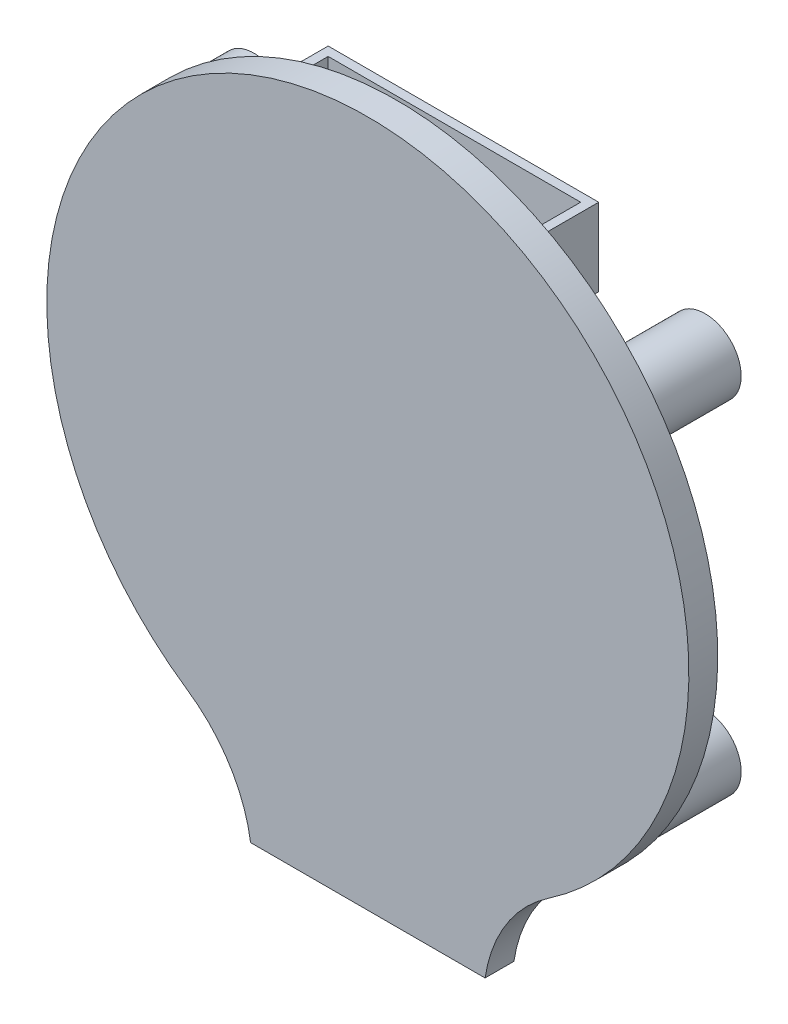
SolidWorks part; units mm, degrees
ref_plane "Plan de face" through (0, 0, 0) normal (0, 0, 1) x (1, 0, 0)
ref_plane "Plan de dessus" through (0, 0, 0) normal (0, 1, 0) x (1, 0, 0)
ref_plane "Plan de droite" through (0, 0, 0) normal (1, 0, 0) x (0, 0, -1)
sketch "Contour_Écran" plane through (0, 0, 0) normal (0, 0, 1) x (1, 0, 0)
  line L0 (10.0051, 0) -> (10.0051, -22.8841) construction
  line L5 (0, 0) -> (10.0051, 0) construction
  line L6 (0, 0) -> (-10.0051, 0) construction
  line L7 (-10.0051, 0) -> (-10.0051, -22.8841) construction
  line L8 (-6.5, -20.3) -> (6.5, -20.3) construction
  line L9 (0, 0) -> (-10.0051, -14.722) construction
  line L10 (0, 0) -> (10.0051, -14.722) construction
  line L11 (-6.5, -20.3) -> (6.5, -20.3)
  line L12 (0, 0) -> (-6.5, -20.3) construction
  line L13 (0, 0) -> (6.5, -20.3) construction
  arc A0 (10.0051, -14.722) -> (-10.0051, -14.722) centre (0, 0) ccw
  arc A1 (-10.0051, -14.722) -> (-6.5, -20.3) centre (-14.6194, -21.5118) cw
  arc A2 (10.0051, -14.722) -> (6.5, -20.3) centre (14.6194, -21.5118) ccw
  point P4 (0, -20.3)
  dimension "D1" = 17.8
  dimension "D2" = 13
  dimension "D3" = 20.3
  dimension "D4" = 55.8
  dimension "D5" = 55.8
extrude "Boss.-Extru.1_Contour_Écran" add sketch "Contour_Écran" along normal blind 1.6
sketch "Entretoises" plane through (0, 0, 0) normal (0, 0, -1) x (-1, 0, 0)
  line L1 (-12.5, -9.5) -> (12.5, -9.5) construction
  line L2 (-12.5, -9.5) -> (-12.5, 9.5) construction
  line L3 (-12.5, 9.5) -> (12.5, 9.5) construction
  line L4 (12.5, -9.5) -> (12.5, 9.5) construction
  line L5 (-12.5, -9.5) -> (12.5, 9.5) construction
  line L6 (-12.5, 9.5) -> (12.5, -9.5) construction
  circle A0 centre (-12.5, 9.5) radius 2
  circle A1 centre (12.5, 9.5) radius 2
  circle A2 centre (12.5, -9.5) radius 2
  circle A3 centre (-12.5, -9.5) radius 2
  point P0 (0, 0)
  dimension "D3" = 4
  dimension "D1" = 19
  dimension "D2" = 25
  dimension "D4" = 2
  dimension "D5" = 2
extrude "Boss.-Extru.1_Entretoises" add sketch "Entretoises" along normal blind 4.6
sketch "Trous_Vis_M2" plane through (0, 0, -4.6) normal (0, 0, -1) x (-1, 0, 0)
  circle A0 centre (-12.5, 9.5) radius 1
  circle A1 centre (12.5, 9.5) radius 1
  circle A2 centre (12.5, -9.5) radius 1
  circle A3 centre (-12.5, -9.5) radius 1
  dimension "D1" = 2
  dimension "D2" = 2
  dimension "D3" = 2
extrude "Enlèv. mat.-Extru.1_Trous_Vis_M2" cut sketch "Trous_Vis_M2" against normal up to surface (4.6 mm away) up to face at (10.5, -9.5, 0)
sketch "Connecteurs_Blancs" plane through (0, 0, 0) normal (0, 0, -1) x (-1, 0, 0)
  line L0 (-24.5608, 17.8) -> (30.8028, 17.8) construction
  line L1 (-7.5, 10.5) -> (7.5, 10.5)
  line L2 (-7.5, 10.5) -> (-7.5, 14.8)
  line L3 (-7.5, 14.8) -> (7.5, 14.8)
  line L4 (7.5, 10.5) -> (7.5, 14.8)
  line L5 (-7.5, 10.5) -> (7.5, 14.8) construction
  line L6 (-7.5, 14.8) -> (7.5, 10.5) construction
  line L7 (-5, -8.3) -> (5, -8.3)
  line L8 (-5, -8.3) -> (-5, -4)
  line L9 (-5, -4) -> (5, -4)
  line L10 (5, -8.3) -> (5, -4)
  line L11 (-5, -8.3) -> (5, -4) construction
  line L12 (-5, -4) -> (5, -8.3) construction
  line L13 (0, 17.8) -> (0, 14.8) construction
  line L14 (0, 10.5) -> (0, -4) construction
  circle A0 centre (0, 0) radius 17.8 construction
  arc A1 (10.0051, -14.722) -> (-10.0051, -14.722) centre (0, 0) ccw construction
  point P0 (0, 12.65)
  point P5 (0, -6.15)
  point P20 (0, 14.8)
  point P23 (0, -4)
  dimension "D1" = 4.3
  dimension "D2" = 10
  dimension "D3" = 4.3
  dimension "D4" = 15
  dimension "D5" = 3
  dimension "D6" = 14.5
extrude "Boss.-Extru.2_Connecteurs_Blancs" add sketch "Connecteurs_Blancs" along normal blind 3.7
sketch "Ouverture_gros_connecteur_blanc" plane through (0, 14.8, 0) normal (0, 1, 0) x (1, 0, 0)
  line L0 (-7.5, 3.7) -> (7.5, 0) construction
  line L1 (-7.5, 0) -> (7.5, 3.7) construction
  line L2 (-7.5, 3.7) -> (7.5, 3.7) construction
  line L3 (-7, 0.5) -> (7, 0.5)
  line L4 (-7, 0.5) -> (-7, 3.2)
  line L5 (-7, 3.2) -> (7, 3.2)
  line L6 (7, 0.5) -> (7, 3.2)
  line L7 (-7, 0.5) -> (7, 3.2) construction
  line L8 (-7, 3.2) -> (7, 0.5) construction
  line L9 (-7.5, 3.7) -> (-7.5, 0) construction
  point P8 (0, 1.85)
  dimension "D1" = 0.5
  dimension "D2" = 0.5
extrude "Enlèv. mat.-Extru.2_Ouverture_gros_connecteur_blanc" cut sketch "Ouverture_gros_connecteur_blanc" against normal blind 3.7
sketch "Ouverture_petit_connecteur_blanc" plane through (0, -4, 0) normal (0, 1, 0) x (1, 0, 0)
  line L0 (-5, 3.7) -> (5, 0) construction
  line L1 (-5, 3.7) -> (5, 3.7) construction
  line L2 (-5, 3.7) -> (-5, 0) construction
  line L3 (-5, 0) -> (5, 3.7) construction
  line L5 (-4.5, 0.5) -> (4.5, 0.5)
  line L6 (-4.5, 0.5) -> (-4.5, 3.2)
  line L7 (-4.5, 3.2) -> (4.5, 3.2)
  line L8 (4.5, 0.5) -> (4.5, 3.2)
  line L9 (-4.5, 0.5) -> (4.5, 3.2) construction
  line L10 (-4.5, 3.2) -> (4.5, 0.5) construction
  point P11 (0, 1.85)
  dimension "D1" = 0.5
  dimension "D2" = 0.5
extrude "Enlèv. mat.-Extru.3_Ouverture_petit_connecteur_blanc" cut sketch "Ouverture_petit_connecteur_blanc" against normal blind 3.7
